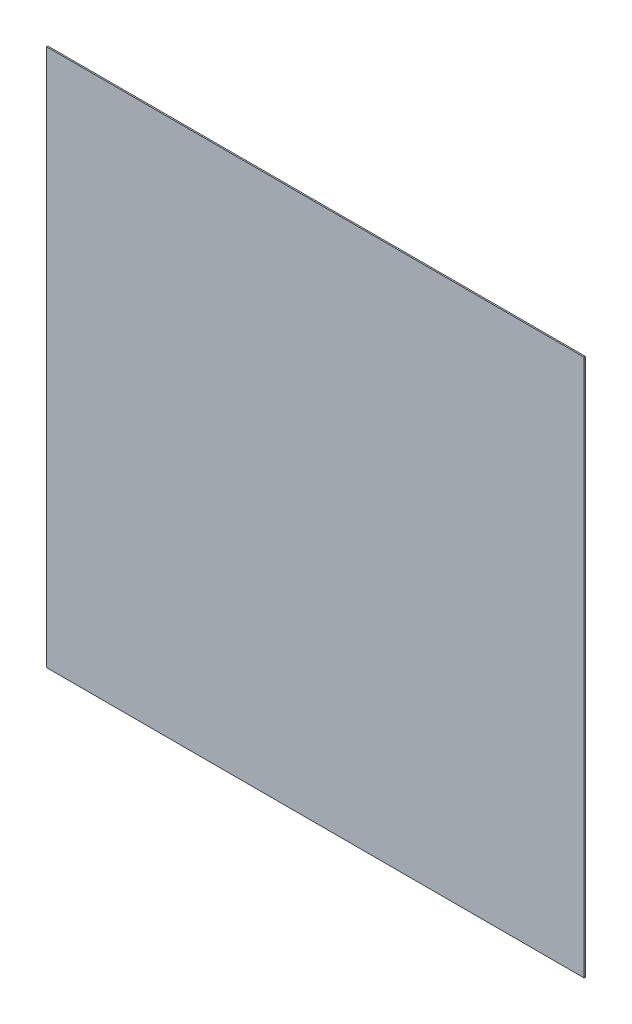
SolidWorks part; units mm, degrees
ref_plane "Front Plane" through (0, 0, 0) normal (0, 0, 1) x (1, 0, 0)
ref_plane "Top Plane" through (0, 0, 0) normal (0, 1, 0) x (1, 0, 0)
ref_plane "Right Plane" through (0, 0, 0) normal (1, 0, 0) x (0, 0, -1)
sketch "Sketch1" plane through (0, 0, 0) normal (0, 0, 1) x (1, 0, 0)
  line L1 (-25.4, 25.4) -> (25.4, 25.4)
  line L2 (-25.4, 25.4) -> (-25.4, -25.4)
  line L3 (-25.4, -25.4) -> (25.4, -25.4)
  line L4 (25.4, 25.4) -> (25.4, -25.4)
  line L5 (-25.4, 25.4) -> (25.4, -25.4) construction
  line L6 (-25.4, -25.4) -> (25.4, 25.4) construction
  point P0 (0, 0)
extrude "Boss-Extrude1" add sketch "Sketch1" along normal blind 0.127
